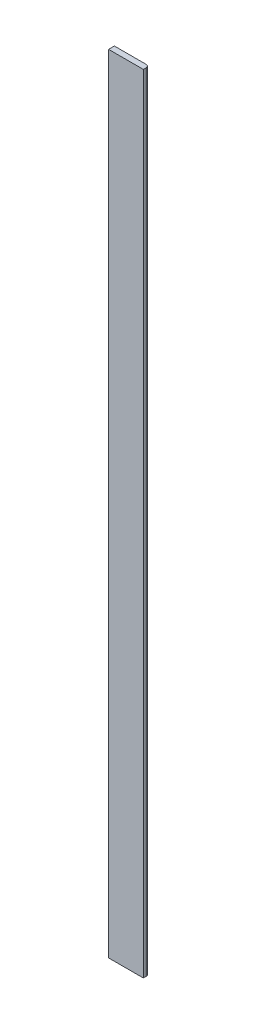
SolidWorks part; units mm, degrees
material "6061 Alloy"
ref_plane "Front Plane" through (0, 0, 0) normal (0, 0, 1) x (1, 0, 0)
ref_plane "Top Plane" through (0, 0, 0) normal (0, 1, 0) x (1, 0, 0)
ref_plane "Right Plane" through (0, 0, 0) normal (1, 0, 0) x (0, 0, -1)
sketch "Sketch2" plane through (0, 0, 0) normal (0, 1, 0) x (1, 0, 0)
  line L0 (0, 0) -> (19.05, 0)
  line L1 (0, 0) -> (0, 19.05)
  line L2 (4.7625, 3.175) -> (17.4625, 3.175)
  line L3 (3.175, 4.7625) -> (3.175, 17.4625)
  line L4 (0, 19.05) -> (1.5875, 19.05)
  line L5 (19.05, 1.5875) -> (19.05, 0)
  line L6 (3.175, 3.175) -> (3.175, 19.05) construction
  line L7 (3.175, 3.175) -> (19.05, 3.175) construction
  arc A0 (3.175, 17.4625) -> (1.5875, 19.05) centre (1.5875, 17.4625) ccw
  arc A1 (3.175, 4.7625) -> (4.7625, 3.175) centre (4.7625, 4.7625) ccw
  arc A2 (17.4625, 3.175) -> (19.05, 1.5875) centre (17.4625, 1.5875) cw
  dimension "D2" = 1.5875
  dimension "D1" = 3.175
extrude "Boss-Extrude1" add sketch "Sketch2" along normal blind 431.8
sketch "Sketch3" plane through (0, 0, -3.175) normal (0, 0, -1) x (-1, 0, 0)
  line L0 (-19.05, 0) -> (-3.175, 0) construction
  line L1 (-11.1125, 0) -> (-11.1125, 15.875) construction
  circle A0 centre (-11.1125, 7.9375) radius 1.688
sketch "Sketch4" plane through (3.175, 0, 0) normal (1, 0, 0) x (0, 0, -1)
  line L0 (19.05, 431.8) -> (19.05, 406.4)
  line L1 (19.05, 431.8) -> (19.05, 0) construction
  line L2 (19.05, 406.4) -> (3.175, 406.4)
  line L3 (3.175, 431.8) -> (3.175, 0) construction
  line L4 (3.175, 406.4) -> (3.175, 431.8)
  line L5 (3.175, 431.8) -> (19.05, 431.8)
extrude "Cut-Extrude1" cut sketch "Sketch4" against normal blind 6.35
sketch "Sketch5" plane through (3.175, 0, 0) normal (-1, 0, 0) x (0, 0, 1)
  line L8 (-4.7625, 406.4) -> (-3.175, 406.4)
  line L9 (-3.175, 406.4) -> (-3.175, 431.8)
  line L10 (-3.175, 431.8) -> (-4.7625, 431.8)
  line L11 (-4.7625, 431.8) -> (-4.7625, 406.4)
  line L12 (-4.7625, 406.4) -> (-3.175, 406.4)
  line L13 (-3.175, 406.4) -> (-3.175, 431.8)
  line L14 (-3.175, 431.8) -> (-4.7625, 431.8)
  line L15 (-4.7625, 431.8) -> (-4.7625, 406.4)
  dimension "D1" = 0
extrude "Cut-Extrude2" cut sketch "Sketch5" against normal blind 6.35
